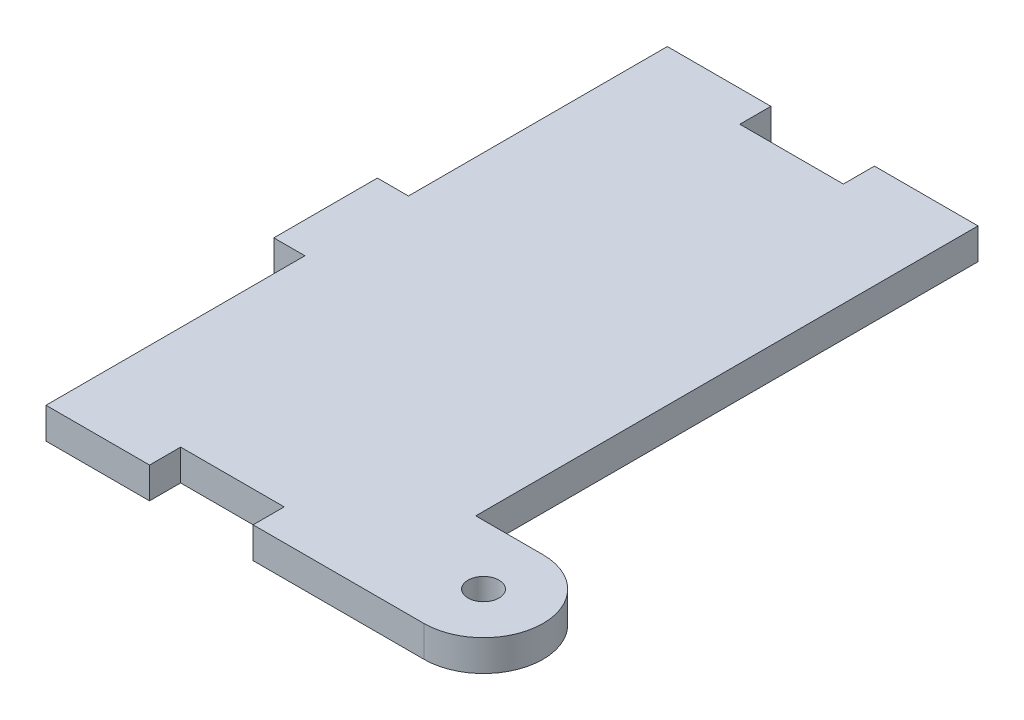
SolidWorks part; units mm, degrees
ref_plane "Front Plane" through (0, 0, 0) normal (0, 0, 1) x (1, 0, 0)
ref_plane "Top Plane" through (0, 0, 0) normal (0, 1, 0) x (1, 0, 0)
ref_plane "Right Plane" through (0, 0, 0) normal (1, 0, 0) x (0, 0, -1)
sketch "Sketch1" plane through (0, 0, 0) normal (0, 1, 0) x (1, 0, 0)
  line L0 (21.5, -18.5) -> (15, -18.5)
  line L1 (15, 30) -> (5, 30)
  line L2 (15, 30) -> (15, -5)
  line L3 (15, -30) -> (5, -30)
  line L4 (-15, 30) -> (-15, 5)
  line L5 (15, 30) -> (-15, -30) construction
  line L6 (15, -30) -> (-15, 30) construction
  line L7 (21.5, -30) -> (15, -30)
  line L8 (-5, 30) -> (-15, 30)
  line L9 (-15, -5) -> (-15, -30)
  line L10 (-5, 30) -> (-5, 27)
  line L11 (-5, 27) -> (5, 27)
  line L12 (5, 30) -> (5, 27)
  line L13 (-15, 5) -> (-18, 5)
  line L14 (15, -5) -> (15, -18.5)
  line L15 (-15, -5) -> (-18, -5)
  line L16 (-18, 5) -> (-18, -5)
  line L18 (-5, -30) -> (-15, -30)
  line L22 (-5, -30) -> (-5, -27)
  line L23 (-5, -27) -> (5, -27)
  line L24 (5, -30) -> (5, -27)
  arc A0 (21.5, -30) -> (21.5, -18.5) centre (21.5, -24.25) ccw
  circle A1 centre (21.5, -24.25) radius 1.5
  point P0 (0, 0)
  dimension "D3" = 11.5
  dimension "D9" = 3
  dimension "D12" = 10
  dimension "D1" = 60
  dimension "D2" = 30
  dimension "D4" = 36.5
  dimension "D5" = 10
  dimension "D6" = 3
  dimension "D7" = 10
  dimension "D8" = 25
  dimension "D10" = 3
  dimension "D11" = 10
extrude "Boss-Extrude1" add sketch "Sketch1" along normal blind 3
